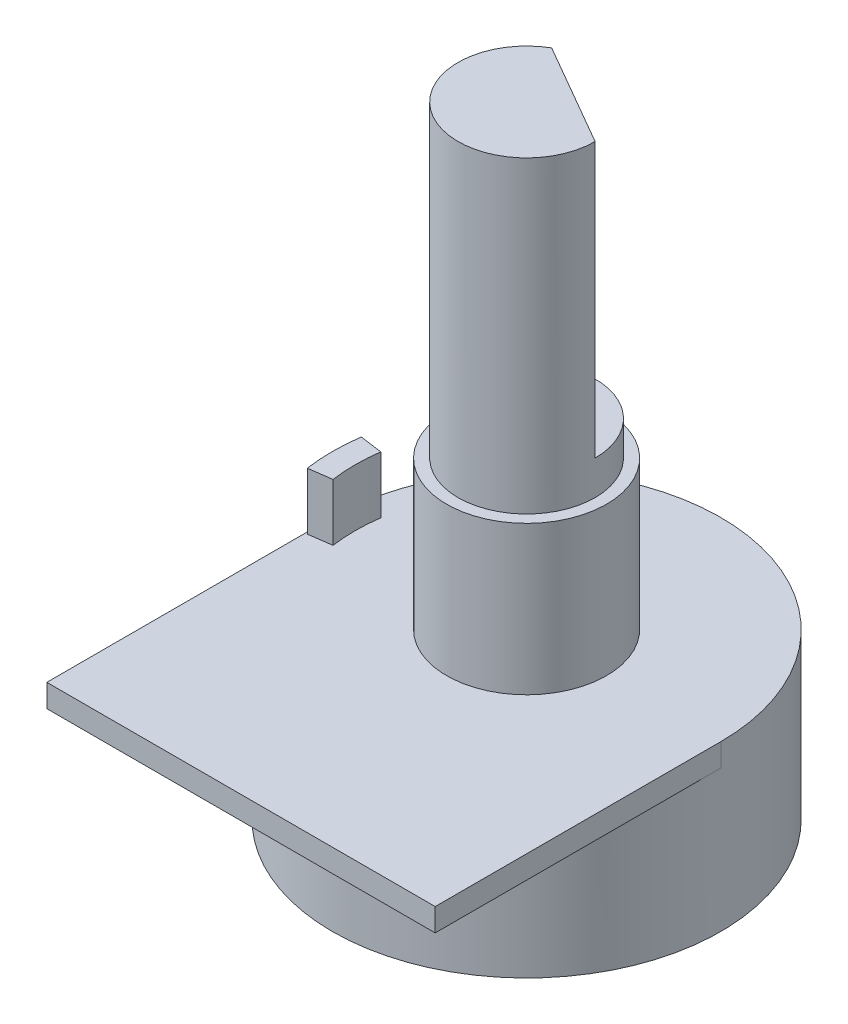
SolidWorks part; units mm, degrees
ref_plane "前视基准面" through (0, 0, 0) normal (0, 0, 1) x (1, 0, 0)
ref_plane "上视基准面" through (0, 0, 0) normal (0, 1, 0) x (1, 0, 0)
ref_plane "右视基准面" through (0, 0, 0) normal (1, 0, 0) x (0, 0, -1)
other "Configuration Table"
sketch "草图1" plane through (0, 0, 0) normal (0, 1, 0) x (1, 0, 0)
  circle A1 centre (0, 0) radius 8.5
extrude "凸台-拉伸1" add sketch "草图1" along normal blind 7.2
sketch "草图2" plane through (0, 7.2, 0) normal (0, 1, 0) x (1, 0, 0)
  line L0 (0, 0) -> (19.3248, 0) construction
  line L3 (-7.427, 1.0438) -> (-8.4173, 1.183)
  line L4 (-7.427, -1.0438) -> (-8.4173, -1.183)
  arc A2 (-7.427, 1.0438) -> (-7.427, -1.0438) centre (0, 0) ccw
  circle A5 centre (0, 0) radius 8.5
  arc A6 (-8.4173, 1.183) -> (-8.4173, -1.183) centre (0, 0) ccw
  dimension "D5" = 15
  dimension "D6" = 0
  dimension "D7" = 8
  dimension "D8" = 8
extrude "凸台-拉伸2" add sketch "草图2" along normal blind 2.5
sketch "草图3" plane through (0, 7.2, 0) normal (0, 1, 0) x (1, 0, 0)
  circle A0 centre (0, 0) radius 3.5
  dimension "D1" = 7
extrude "凸台-拉伸3" add sketch "草图3" along normal blind 6.5
sketch "草图4" plane through (0, 13.7, 0) normal (0, 1, 0) x (1, 0, 0)
  circle A0 centre (0, 0) radius 3
  dimension "D1" = 6
extrude "凸台-拉伸4" add sketch "草图4" along normal blind 13.5
sketch "草图5" plane through (0, 27.2, 0) normal (0, 1, 0) x (1, 0, 0)
  line L0 (0, 0) -> (3.2119, 5.5632) construction
  line L1 (0, 0) -> (5.2468, 0) construction
  line L2 (-1.5, 2.5981) -> (3, 0)
  circle A1 centre (0, 0) radius 3
  arc A2 (3, 0) -> (-1.5, 2.5981) centre (0, 0) ccw
  dimension "D2" = 60
  dimension "D1" = 0
extrude "切除-拉伸1" cut sketch "草图5" against normal blind 12
sketch "草图6" plane through (0, 7.2, 0) normal (0, 1, 0) x (1, 0, 0)
  line L1 (8.5, 0) -> (-8.5, 0)
  line L2 (8.5, 0) -> (8.5, -12.5)
  line L3 (8.5, -12.5) -> (-8.5, -12.5)
  line L4 (-8.5, 0) -> (-8.5, -12.5)
  arc A0 (-8.4173, -1.183) -> (-8.4173, 1.183) centre (0, 0) ccw construction
  dimension "D1" = 12.5
extrude "凸台-拉伸5" add sketch "草图6" against normal blind 1
